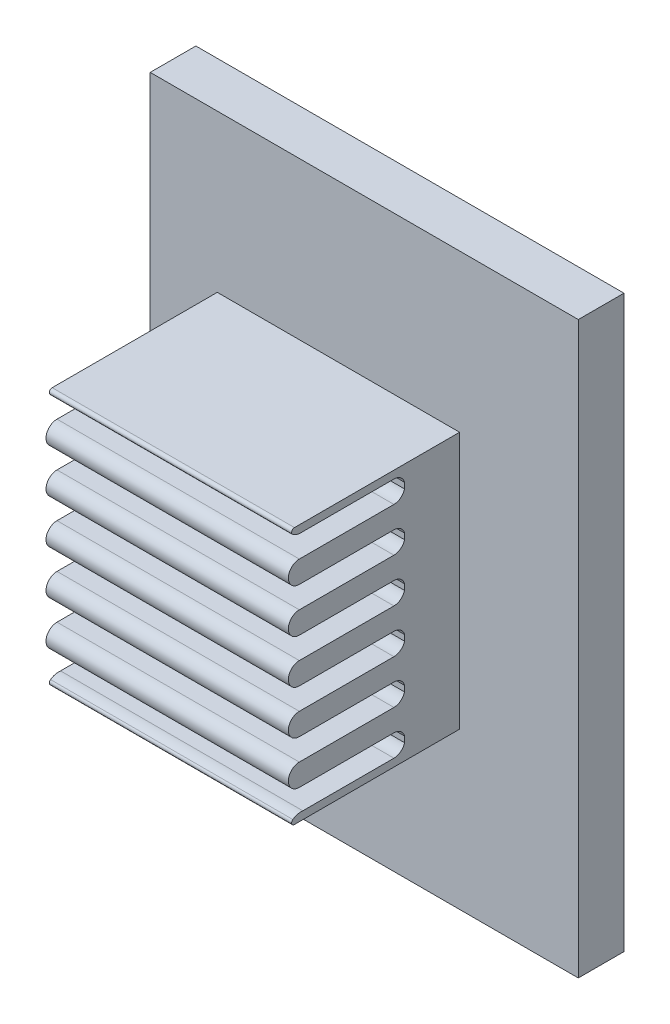
SolidWorks part; units mm, degrees
ref_plane "Alzado" through (0, 0, 0) normal (0, 0, 1) x (1, 0, 0)
ref_plane "Planta" through (0, 0, 0) normal (0, 1, 0) x (1, 0, 0)
ref_plane "Vista lateral" through (0, 0, 0) normal (1, 0, 0) x (0, 0, -1)
sketch "Croquis1" plane through (0, 0, 0) normal (0, 0, 1) x (1, 0, 0)
  line L1 (-7.5, 9.99) -> (7.5, 9.99)
  line L2 (-7.5, 9.99) -> (-7.5, -9.99)
  line L3 (-7.5, -9.99) -> (7.5, -9.99)
  line L4 (7.5, 9.99) -> (7.5, -9.99)
extrude "Saliente-Extruir1" add sketch "Croquis1" along normal blind 1.6
sketch "Croquis2" plane through (0, 0, 1.6) normal (0, 0, 1) x (1, 0, 0)
  line L5 (-5.15, -4.52) -> (3.34, -4.52)
  line L6 (-5.15, -4.52) -> (-5.15, 4.49)
  line L7 (-5.15, 4.49) -> (3.34, 4.49)
  line L8 (3.34, -4.52) -> (3.34, 4.49)
extrude "Saliente-Extruir2" add sketch "Croquis2" along normal blind 6
sketch "Croquis3" plane through (-5.15, 0, 0) normal (-1, 0, 0) x (0, 0, 1)
  line L0 (7.215, 0.37) -> (3.9, 0.37)
  line L1 (3.9, -4.25) -> (7.215, -4.25)
  line L2 (7.215, -3.48) -> (3.9, -3.48)
  line L3 (3.9, -2.71) -> (7.215, -2.71)
  line L4 (7.215, -1.94) -> (3.9, -1.94)
  line L5 (7.6, -4.52) -> (1.6, -4.52) construction
  line L6 (3.9, 1.14) -> (7.215, 1.14)
  line L7 (3.9, -1.17) -> (7.215, -1.17)
  line L8 (7.215, 1.91) -> (3.9, 1.91)
  line L9 (7.215, -0.4) -> (3.9, -0.4)
  line L10 (3.9, 2.68) -> (7.215, 2.68)
  line L11 (7.6, 4.49) -> (3.5283, 4.49)
  line L12 (7.215, 3.45) -> (3.9, 3.45)
  line L13 (7.6, 4.49) -> (7.6, -4.52)
  line L14 (3.9, 4.22) -> (7.215, 4.22)
  line L15 (7.6, -4.52) -> (3.5283, -4.52)
  line L16 (3.5283, 4.49) -> (3.5283, -4.52)
  arc A0 (7.215, -0.4) -> (7.215, 0.37) centre (7.215, -0.015) ccw
  arc A1 (3.9, 1.14) -> (3.9, 0.37) centre (3.9, 0.755) ccw
  arc A2 (7.215, 1.14) -> (7.215, 1.91) centre (7.215, 1.525) ccw
  arc A3 (3.9, 2.68) -> (3.9, 1.91) centre (3.9, 2.295) ccw
  arc A4 (7.215, 2.68) -> (7.215, 3.45) centre (7.215, 3.065) ccw
  arc A5 (3.9, 4.22) -> (3.9, 3.45) centre (3.9, 3.835) ccw
  arc A6 (7.0911, 4.22) -> (7.6, 4.49) centre (7.153, 4.7179) ccw
  arc A7 (7.0911, -4.25) -> (7.6, -4.52) centre (7.153, -4.7479) cw
  arc A8 (3.9, -4.25) -> (3.9, -3.48) centre (3.9, -3.865) cw
  arc A9 (7.215, -2.71) -> (7.215, -3.48) centre (7.215, -3.095) cw
  arc A10 (3.9, -2.71) -> (3.9, -1.94) centre (3.9, -2.325) cw
  arc A11 (7.215, -1.17) -> (7.215, -1.94) centre (7.215, -1.555) cw
  arc A12 (3.9, -1.17) -> (3.9, -0.4) centre (3.9, -0.785) cw
  line M19 (7.6, -4.52) -> (7.6, 4.49)
extrude "Cortar-Extruir1" cut sketch "Croquis3" against normal through all contours A6 L14 A5 L16 L12 A4 L13 | A4 L10 A3 L16 L8 A2 M19 | A2 L6 A1 L16 L0 A0 L13 | A12 L7 A11 A0 L9 L16 M19 | L13 A11 L4 A10 L16 L3 A9 | A9 L2 A8 L16 L1 A7 M19
fillet "Redondeo1" radius 0.1 1 edges at (-0.905, -4.52, 7.6)
fillet "Redondeo2" radius 0.1 1 edges at (-0.905, 4.49, 7.6)
